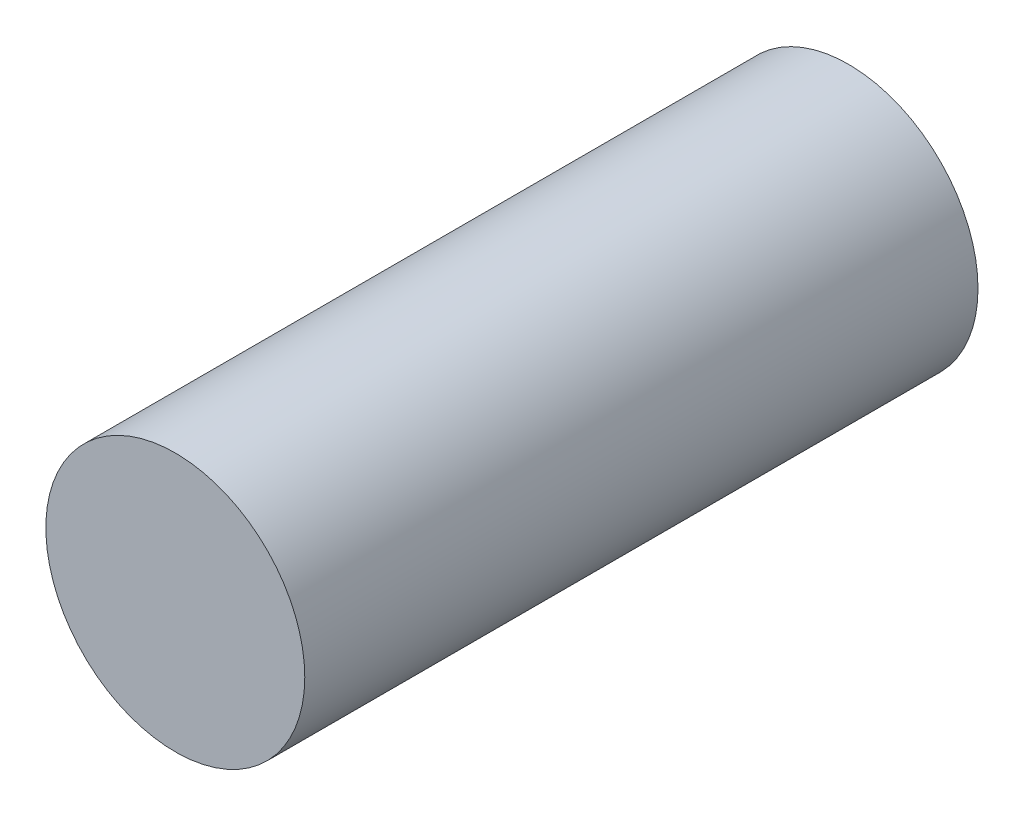
SolidWorks part; units mm, degrees
ref_plane "前视基准面" through (0, 0, 0) normal (0, 0, 1) x (1, 0, 0)
ref_plane "上视基准面" through (0, 0, 0) normal (0, 1, 0) x (1, 0, 0)
ref_plane "右视基准面" through (0, 0, 0) normal (1, 0, 0) x (0, 0, -1)
sketch "草图1" plane through (0, 0, 0) normal (0, 0, 1) x (1, 0, 0)
  circle A0 centre (0, 0) radius 2.5
extrude "凸台-拉伸1" add sketch "草图1" along normal blind 20
sketch "草图2" plane through (0, 0, 20) normal (0, 0, 1) x (1, 0, 0)
  circle A0 centre (0, 0) radius 2.5
extrude "切除-拉伸1" cut sketch "草图2" against normal blind 7
